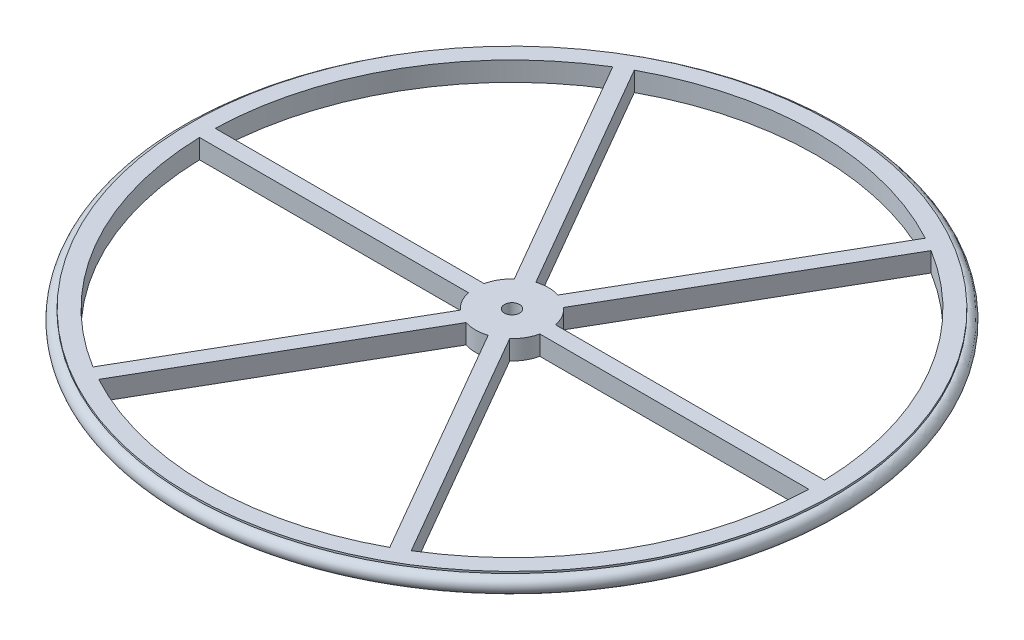
SolidWorks part; units mm, degrees
ref_plane "Front Plane" through (0, 0, 0) normal (0, 0, 1) x (1, 0, 0)
ref_plane "Top Plane" through (0, 0, 0) normal (0, 1, 0) x (1, 0, 0)
ref_plane "Right Plane" through (0, 0, 0) normal (1, 0, 0) x (0, 0, -1)
sketch "Sketch1" plane through (0, 0, 0) normal (0, 1, 0) x (1, 0, 0)
  line L0 (-175.7, 0) -> (175.7, 0) construction
  line L1 (0, -175.7) -> (0, 175.7) construction
  line L2 (-19.5323, 4.3) -> (-166.4, 4.3)
  line L3 (-19.5323, -4.3) -> (-166.4, -4.3)
  line L4 (-6.0422, 19.0655) -> (-79.4761, 146.2566)
  line L5 (-13.49, 14.7655) -> (-86.9239, 141.9566)
  line L6 (13.49, 14.7655) -> (86.9239, 141.9566)
  line L7 (6.0422, 19.0655) -> (79.4761, 146.2566)
  line L8 (19.5323, -4.3) -> (166.4, -4.3)
  line L9 (19.5323, 4.3) -> (166.4, 4.3)
  line L10 (6.0422, -19.0655) -> (79.4761, -146.2566)
  line L11 (13.49, -14.7655) -> (86.9239, -141.9566)
  line L12 (-13.49, -14.7655) -> (-86.9239, -141.9566)
  line L13 (-6.0422, -19.0655) -> (-79.4761, -146.2566)
  circle A0 centre (0, 0) radius 4.125
  arc A1 (19.5323, 4.3) -> (13.49, 14.7655) centre (0, 0) ccw
  circle A2 centre (0, 0) radius 175.7 construction
  arc A3 (-86.9239, 141.9566) -> (-166.4, 4.3) centre (0, 0) ccw
  arc A4 (79.4761, 146.2566) -> (-79.4761, 146.2566) centre (0, 0) ccw
  arc A5 (86.9239, 141.9566) -> (166.4, 4.3) centre (0, 0) cw
  arc A6 (166.4, -4.3) -> (86.9239, -141.9566) centre (0, 0) cw
  arc A7 (79.4761, -146.2566) -> (-79.4761, -146.2566) centre (0, 0) cw
  arc A8 (-166.4, -4.3) -> (-86.9239, -141.9566) centre (0, 0) ccw
  circle A9 centre (0, 0) radius 175.7
  arc A10 (6.0422, 19.0655) -> (-6.0422, 19.0655) centre (0, 0) ccw
  arc A11 (-13.49, 14.7655) -> (-19.5323, 4.3) centre (0, 0) ccw
  arc A12 (-19.5323, -4.3) -> (-13.49, -14.7655) centre (0, 0) ccw
  arc A13 (-6.0422, -19.0655) -> (6.0422, -19.0655) centre (0, 0) ccw
  arc A14 (13.49, -14.7655) -> (19.5323, -4.3) centre (0, 0) ccw
  point P35 (0, 0)
  dimension "D1" = 8.25
  dimension "D2" = 40
  dimension "D3" = 351.4
  dimension "D4" = 8.6
  dimension "D5" = 166.4
  dimension "D6" = 6
extrude "Boss-Extrude1" add sketch "Sketch1" along normal blind 10.6
sketch "Sketch3" plane through (0, 0, 0) normal (0, 0, 1) x (1, 0, 0)
  line L1 (0, 0) -> (0, 16.7475) construction
  line L3 (175.7, 0) -> (175.7, 10.6) construction
  circle A1 centre (175.7, 5.3) radius 4.3
  dimension "D1" = 8.6
revolve "Cut-Revolve1" cut sketch "Sketch3" angle 360 about L1
sketch "Sketch5" plane through (0, 0, 0) normal (1, 0, 0) x (0, 0, -1)
  line L0 (0, 0) -> (0, 29.9636) construction
  line L1 (-175.7, 0) -> (175.7, 0) construction
  circle A0 centre (175.7, 5.3) radius 4.3
  arc A1 (175.7, 9.6) -> (175.7, 1) centre (175.7, 5.3) ccw construction
  dimension "D1" = 8.6
revolve "Revolve1" add sketch "Sketch5" angle 360 about L0
